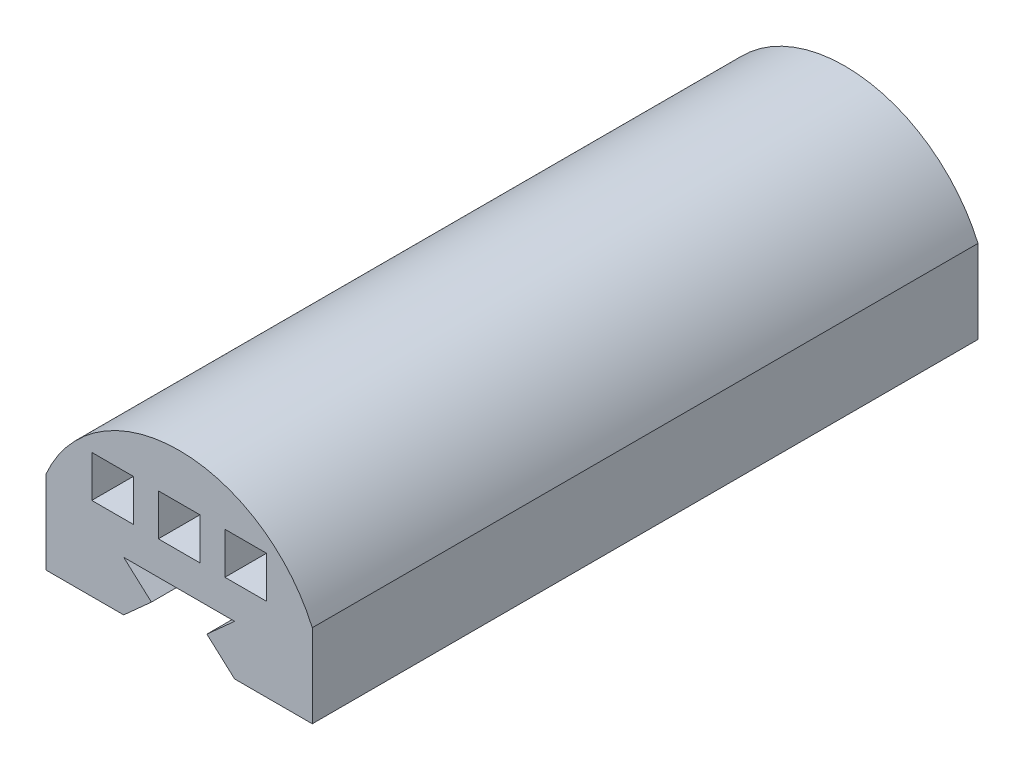
SolidWorks part; units mm, degrees
material "PET"
ref_plane "Front Plane" through (0, 0, 0) normal (0, 0, 1) x (1, 0, 0)
ref_plane "Top Plane" through (0, 0, 0) normal (0, 1, 0) x (1, 0, 0)
ref_plane "Right Plane" through (0, 0, 0) normal (1, 0, 0) x (0, 0, -1)
sketch "Sketch1" plane through (0, 0, 0) normal (0, 1, 0) x (1, 0, 0)
  line L1 (-10.16, 25.4) -> (10.16, 25.4)
  line L2 (-10.16, 25.4) -> (-10.16, -25.4)
  line L3 (-10.16, -25.4) -> (10.16, -25.4)
  line L4 (10.16, 25.4) -> (10.16, -25.4)
  line L5 (-10.16, 25.4) -> (10.16, -25.4) construction
  line L6 (-10.16, -25.4) -> (10.16, 25.4) construction
  point P0 (0, 0)
  dimension "D1" = 20.32
  dimension "D2" = 50.8
extrude "Boss-Extrude1" add sketch "Sketch1" along normal blind 19.05 contours L2 L3 L4 L1
sketch "Sketch3" plane through (0, 0, 25.4) normal (0, 0, 1) x (1, 0, 0)
  line L0 (-10.16, 0) -> (10.16, 0) construction
  line L1 (-4.2333, 3.81) -> (4.2333, 3.81) construction
  line L2 (-4.2333, 3.81) -> (-4.2333, 0) construction
  line L3 (-4.2333, 0) -> (4.2333, 0) construction
  line L4 (4.2333, 3.81) -> (4.2333, 0) construction
  line L5 (-4.2333, 3.81) -> (4.2333, 0) construction
  line L6 (-4.2333, 0) -> (4.2333, 3.81) construction
  line L7 (-4.2333, 1.905) -> (0, 1.905) construction
  line L8 (0, 1.905) -> (0, 3.81) construction
  line L9 (-4.2333, 3.81) -> (-2.1167, 1.905) construction
  line L10 (-2.1167, 1.905) -> (-4.2333, 0) construction
  line L11 (-4.2333, 3.81) -> (-4.2333, 0) construction
  line L12 (2.1167, 1.905) -> (4.2333, 0) construction
  line L13 (4.2333, 3.81) -> (4.2333, 0) construction
  line L14 (4.2333, 3.81) -> (2.1167, 1.905) construction
  line L15 (-4.2333, 3.81) -> (4.2333, 3.81)
  line L16 (4.2333, 3.81) -> (2.1167, 1.905)
  line L17 (2.1167, 1.905) -> (4.2333, 0)
  line L18 (4.2333, 0) -> (-4.2333, 0)
  line L19 (-4.2333, 0) -> (-2.1167, 1.905)
  line L20 (-2.1167, 1.905) -> (-4.2333, 3.81)
  point P0 (0, 1.905)
  dimension "D1" = 3.81
  dimension "D2" = 8.4667
extrude "Cut-Extrude1" cut sketch "Sketch3" against normal up to surface (50.8 mm away) up to face at (0, 9.525, -25.4)
sketch "Sketch4" plane through (0, 3.81, 0) normal (0, -1, 0) x (1, 0, 0)
  line L0 (0, -25.4) -> (0, 4.1063) construction
  line L1 (4.2333, -25.4) -> (-4.2333, -25.4) construction
  line L2 (0, 4.1063) -> (0, 4.7413) construction
  line L3 (0, 4.7413) -> (0, 3.4713)
  arc A1 (0, 4.7413) -> (0, 3.4713) centre (0, 4.1063) cw
  dimension "D2" = 0.635
  dimension "D1" = 29.5063
revolve "Revolve1" add sketch "Sketch4" angle 360 about L0
sketch "Sketch5" plane through (0, 0, 25.4) normal (0, 0, 1) x (1, 0, 0)
  line L0 (-2.1167, 1.905) -> (2.1167, 1.905) construction
  line L1 (-10.16, 19.05) -> (-10.16, 0) construction
  line L2 (-10.16, 6.35) -> (10.16, 6.35) construction
  line L3 (10.16, 19.05) -> (10.16, 0) construction
  line L4 (10.16, 6.35) -> (10.16, 0) construction
  line L5 (-10.16, 6.35) -> (-10.16, 19.05)
  line L6 (-10.16, 19.05) -> (10.16, 19.05)
  line L7 (10.16, 19.05) -> (10.16, 6.35)
  line L8 (0, 0) -> (0, 7.9375) construction
  line L9 (-1.5875, 9.525) -> (1.5875, 9.525)
  line L10 (-1.5875, 9.525) -> (-1.5875, 6.35)
  line L11 (-1.5875, 6.35) -> (1.5875, 6.35)
  line L12 (1.5875, 9.525) -> (1.5875, 6.35)
  line L13 (-1.5875, 9.525) -> (1.5875, 6.35) construction
  line L14 (-1.5875, 6.35) -> (1.5875, 9.525) construction
  line L15 (0, 7.9375) -> (5.08, 7.9375) construction
  line L16 (-6.6675, 9.525) -> (-3.4925, 9.525)
  line L17 (-6.6675, 9.525) -> (-6.6675, 6.35)
  line L18 (-6.6675, 6.35) -> (-3.4925, 6.35)
  line L19 (-3.4925, 9.525) -> (-3.4925, 6.35)
  line L20 (-6.6675, 9.525) -> (-3.4925, 6.35) construction
  line L21 (-6.6675, 6.35) -> (-3.4925, 9.525) construction
  line L22 (3.4925, 9.525) -> (6.6675, 9.525)
  line L23 (3.4925, 9.525) -> (3.4925, 6.35)
  line L24 (3.4925, 6.35) -> (6.6675, 6.35)
  line L25 (6.6675, 9.525) -> (6.6675, 6.35)
  line L26 (3.4925, 9.525) -> (6.6675, 6.35) construction
  line L27 (3.4925, 6.35) -> (6.6675, 9.525) construction
  arc A0 (-10.16, 6.35) -> (10.16, 6.35) centre (0, 1.905) cw
  point P12 (0, 7.9375)
  point P27 (-5.08, 7.9375)
  point P32 (5.08, 7.9375)
  dimension "D1" = 6.35
  dimension "D2" = 3.175
  dimension "D3" = 5.08
  dimension "D4" = 5.08
extrude "Cut-Extrude2" cut sketch "Sketch5" against normal up to surface (50.8 mm away) up to face at (0, 4.953, -25.4)
